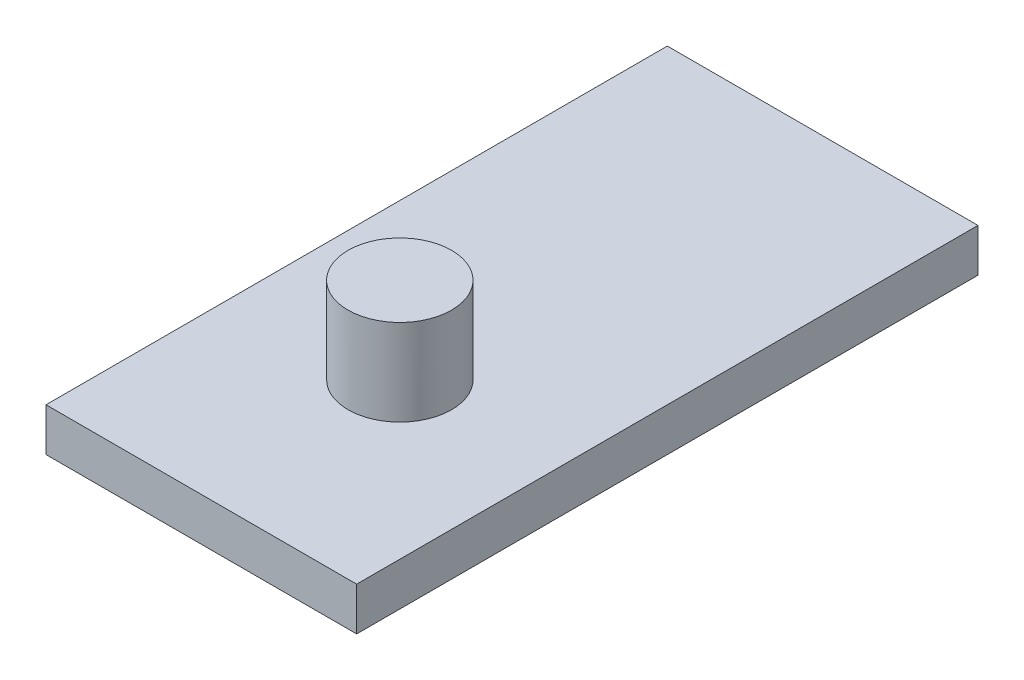
SolidWorks part; units mm, degrees
ref_plane "Front Plane" through (0, 0, 0) normal (0, 0, 1) x (1, 0, 0)
ref_plane "Top Plane" through (0, 0, 0) normal (0, 1, 0) x (1, 0, 0)
ref_plane "Right Plane" through (0, 0, 0) normal (1, 0, 0) x (0, 0, -1)
sketch "Sketch1" plane through (0, 0, 0) normal (0, 1, 0) x (1, 0, 0)
  line L1 (-18, -36) -> (18, -36)
  line L2 (-18, -36) -> (-18, 36)
  line L3 (-18, 36) -> (18, 36)
  line L4 (18, -36) -> (18, 36)
  line L5 (-18, -36) -> (18, 36) construction
  line L6 (-18, 36) -> (18, -36) construction
  point P0 (0, 0)
  dimension "D1" = 36
  dimension "D2" = 72
extrude "Boss-Extrude1" add sketch "Sketch1" along normal blind 5
sketch "Sketch2" plane through (0, 5, 0) normal (0, 1, 0) x (1, 0, 0)
  line L0 (0, 36) -> (0, -36) construction
  line L1 (18, 36) -> (-18, 36) construction
  line L2 (-18, -36) -> (18, -36) construction
  circle A0 centre (0, -13) radius 6
  dimension "D1" = 23
  dimension "D2" = 12
extrude "Boss-Extrude2" add sketch "Sketch2" along normal blind 10
